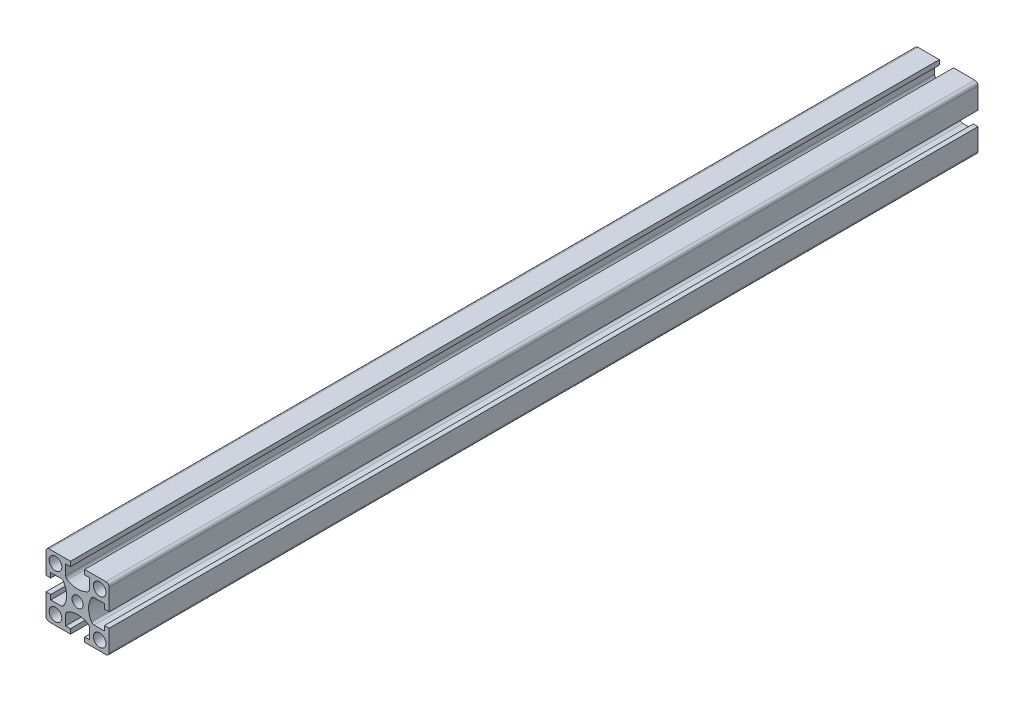
SolidWorks part; units mm, degrees
ref_plane "Front Plane" through (0, 0, 0) normal (0, 0, 1) x (1, 0, 0)
ref_plane "Top Plane" through (0, 0, 0) normal (0, 1, 0) x (1, 0, 0)
ref_plane "Right Plane" through (0, 0, 0) normal (1, 0, 0) x (0, 0, -1)
sketch "Sketch1" plane through (0, 0, 0) normal (0, 0, 1) x (1, 0, 0)
  line L64 (-10, 9) -> (-10, 2.25)
  line L65 (-10, 2.25) -> (-8.5, 2.25)
  line L66 (-8.5, 2.25) -> (-8.5, 3.75)
  line L67 (-8.5, 3.75) -> (-5.2369, 3.75)
  line L68 (-5.2369, -3.75) -> (-8.5, -3.75)
  line L69 (-8.5, -3.75) -> (-8.5, -2.25)
  line L70 (-8.5, -2.25) -> (-10, -2.25)
  line L71 (-10, -2.25) -> (-10, -9)
  line L72 (-9, -10) -> (-2.25, -10)
  line L73 (-2.25, -10) -> (-2.25, -8.5)
  line L74 (-2.25, -8.5) -> (-3.75, -8.5)
  line L75 (-3.75, -8.5) -> (-3.75, -5.2369)
  line L76 (3.75, -5.2369) -> (3.75, -8.5)
  line L77 (3.75, -8.5) -> (2.25, -8.5)
  line L78 (2.25, -8.5) -> (2.25, -10)
  line L79 (2.25, -10) -> (9, -10)
  line L80 (10, -9) -> (10, -2.25)
  line L81 (10, -2.25) -> (8.5, -2.25)
  line L82 (8.5, -2.25) -> (8.5, -3.75)
  line L83 (8.5, -3.75) -> (5.2369, -3.75)
  line L84 (5.2369, 3.75) -> (8.5, 3.75)
  line L85 (8.5, 3.75) -> (8.5, 2.25)
  line L86 (8.5, 2.25) -> (10, 2.25)
  line L87 (10, 2.25) -> (10, 9)
  line L88 (9, 10) -> (2.25, 10)
  line L89 (2.25, 10) -> (2.25, 8.5)
  line L90 (2.25, 8.5) -> (3.75, 8.5)
  line L91 (3.75, 8.5) -> (3.75, 5.2369)
  line L92 (-3.75, 5.2369) -> (-3.75, 8.5)
  line L93 (-3.75, 8.5) -> (-2.25, 8.5)
  line L94 (-2.25, 8.5) -> (-2.25, 10)
  line L95 (-2.25, 10) -> (-9, 10)
  circle A5 centre (-7, -7) radius 2
  circle A6 centre (7, -7) radius 2
  circle A7 centre (7, 7) radius 2
  circle A8 centre (0, 0) radius 1.75
  circle A9 centre (-7, 7) radius 2
  arc A32 (-9, 10) -> (-10, 9) centre (-9, 9) ccw
  arc A33 (-4.3708, 3.25) -> (-5.2369, 3.75) centre (-5.2369, 2.75) ccw
  arc A34 (-4.3708, -3.25) -> (-4.3708, 3.25) centre (-10, 0) ccw
  arc A35 (-5.2369, -3.75) -> (-4.3708, -3.25) centre (-5.2369, -2.75) ccw
  arc A36 (-10, -9) -> (-9, -10) centre (-9, -9) ccw
  arc A37 (-3.25, -4.3708) -> (-3.75, -5.2369) centre (-2.75, -5.2369) ccw
  arc A38 (3.25, -4.3708) -> (-3.25, -4.3708) centre (0, -10) ccw
  arc A39 (3.75, -5.2369) -> (3.25, -4.3708) centre (2.75, -5.2369) ccw
  arc A40 (9, -10) -> (10, -9) centre (9, -9) ccw
  arc A41 (4.3708, -3.25) -> (5.2369, -3.75) centre (5.2369, -2.75) ccw
  arc A42 (4.3708, 3.25) -> (4.3708, -3.25) centre (10, 0) ccw
  arc A43 (5.2369, 3.75) -> (4.3708, 3.25) centre (5.2369, 2.75) ccw
  arc A44 (10, 9) -> (9, 10) centre (9, 9) ccw
  arc A45 (3.25, 4.3708) -> (3.75, 5.2369) centre (2.75, 5.2369) ccw
  arc A46 (-3.25, 4.3708) -> (3.25, 4.3708) centre (0, 10) ccw
  arc A47 (-3.75, 5.2369) -> (-3.25, 4.3708) centre (-2.75, 5.2369) ccw
extrude "Boss-Extrude1" add sketch "Sketch1" along normal blind 275
